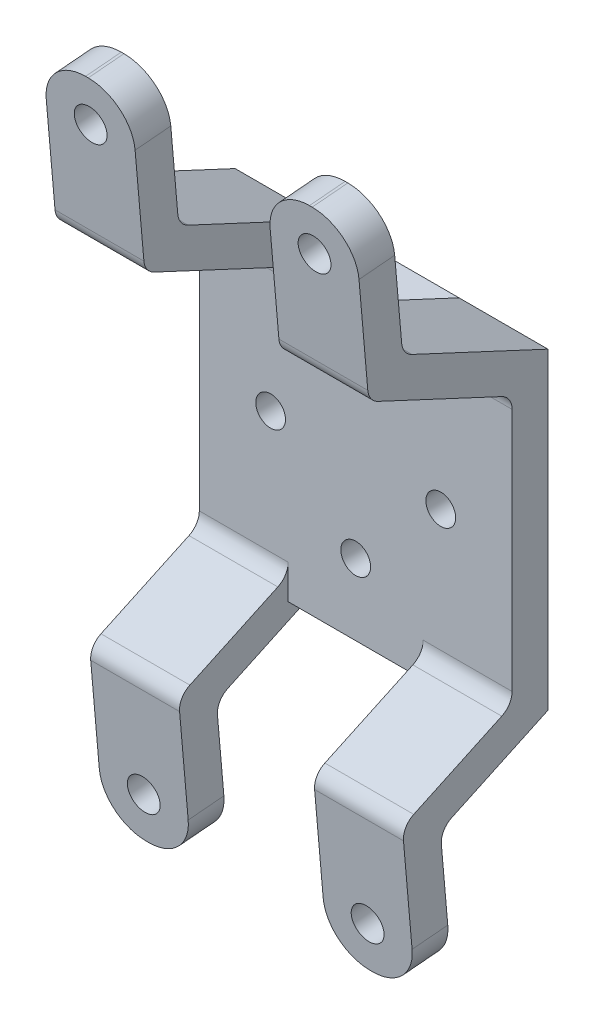
SolidWorks part; units mm, degrees
ref_plane "Front Plane" through (0, 0, 0) normal (0, 0, 1) x (1, 0, 0)
ref_plane "Top Plane" through (0, 0, 0) normal (0, 1, 0) x (1, 0, 0)
ref_plane "Right Plane" through (0, 0, 0) normal (1, 0, 0) x (0, 0, -1)
sketch "Sketch1" plane through (0, 0, 0) normal (0, 0, 1) x (1, 0, 0)
  line L0 (0, 9.5) -> (-9.5, 0) construction
  line L1 (-17.4625, -17.4625) -> (17.4625, -17.4625)
  line L2 (-17.4625, -17.4625) -> (-17.4625, 17.4625)
  line L3 (-17.4625, 17.4625) -> (17.4625, 17.4625)
  line L4 (17.4625, -17.4625) -> (17.4625, 17.4625)
  line L5 (-17.4625, -17.4625) -> (17.4625, 17.4625) construction
  line L6 (-17.4625, 17.4625) -> (17.4625, -17.4625) construction
  line L7 (-9.5, 0) -> (0, -9.5) construction
  line L8 (0, -9.5) -> (9.5, 0) construction
  line L9 (9.5, 0) -> (0, 9.5) construction
  line L10 (0, 9.5) -> (0, -9.5)
  circle A0 centre (0, 9.5) radius 1.6625
  circle A1 centre (9.5, 0) radius 1.6625
  circle A2 centre (-9.5, 0) radius 1.6625
  circle A3 centre (0, -9.5) radius 1.6625
  point P0 (0, 0)
  dimension "D3" = 3.325
  dimension "D1" = 34.925
  dimension "D2" = 19
sketch "Sketch4" plane through (0, 0, 0) normal (1, 0, 0) x (0, 0, -1)
  line L0 (0, 0) -> (-2.8754, 32.8656) construction
  line L1 (0, 19.2087) -> (0, -19.2087) construction
  dimension "D1" = 5
ref_plane "Plane1" through (0, 0, 0) normal (0, 0.0872, -0.9962) x (0, 0.9962, 0.0872)
ref_plane "Plane2" through (0, -0.8716, 9.9619) normal (0, 0.0872, -0.9962) x (0, 0.9962, 0.0872)
extrude "Boss-Extrude4" add sketch "Sketch1" against normal blind 4 separate body
sketch "Sketch7" plane through (-17.4625, 0, 0) normal (-1, 0, 0) x (0, 0, 1)
  line L0 (0, 14.9142) -> (11.8255, 20.4285)
  line L1 (8.0201, -23.0675) -> (6.7627, -37.4389)
  line L2 (-4, 17.4625) -> (12.228, 25.0297)
  line L3 (0, -14.9142) -> (8.391, -18.827)
  line L4 (-4, -17.4625) -> (8.0201, -23.0675)
  line L5 (0, -17.4625) -> (0, 17.4625) construction
  line L6 (11.8255, 20.4285) -> (12.228, 25.0297) construction
  line L9 (8.391, -18.827) -> (8.0201, -23.0675) construction
  line L10 (0, -14.9142) -> (-4, -17.4625)
  line L11 (-4, 17.4625) -> (0, 14.9142)
  line L12 (13.0378, 34.2851) -> (6.8861, -36.0283) construction
  line L13 (12.228, 25.0297) -> (13.5282, 39.8907)
  line L14 (13.5282, 39.8907) -> (17.513, 39.5421)
  line L15 (17.513, 39.5421) -> (16.0115, 22.3805)
  line L16 (16.0115, 22.3805) -> (11.8255, 20.4285)
  line L17 (6.7627, -37.4389) -> (10.7475, -37.7875)
  line L18 (10.7475, -37.7875) -> (12.2489, -20.626)
  line L19 (12.2489, -20.626) -> (8.391, -18.827)
  line M5 (0, -17.4625) -> (0, 17.4625)
  line M6 (0, 17.4625) -> (-4, 17.4625)
  line M8 (-4, -17.4625) -> (0, -17.4625)
  dimension "D1" = 115
  dimension "D2" = 115
  dimension "D3" = 4
  dimension "D4" = 4
  dimension "D5" = 4
  dimension "D6" = 77.625
extrude "Boss-Extrude7" add sketch "Sketch7" against normal blind 9.925 contours L18 L19 L4 L1 L17 M5 M8 | L16 L15 L14 L13 L2 L0 M6 M5
hole_wizard "#6 Clearance Hole1" positions "Sketch8" profile "Sketch9" hole size "#6" standard "ANSI Inch" end condition through all
sketch "Sketch8" plane through (0, -1.2202, 13.9467) normal (0, -0.0872, 0.9962) x (1, 0, 0)
  line L0 (-17.4625, 36.1055) -> (-7.5375, 36.1055) construction
  line L2 (-17.4625, -31.8945) -> (-7.5375, -31.8945) construction
  line L4 (-12.5, 36.1055) -> (-12.5, -31.8945) construction
  line L10 (-12.5, 36.1055) -> (-12.5, 40.918) construction
  line L11 (-7.5375, 40.918) -> (-17.4625, 40.918) construction
  line L13 (-12.5, -31.8945) -> (-12.5, -36.707) construction
  line L14 (-7.5375, -36.707) -> (-17.4625, -36.707) construction
  line L15 (-17.4625, -36.707) -> (-17.4625, -19.4799) construction
  line L16 (-7.5375, -36.707) -> (-7.5375, -19.4799) construction
  line L17 (-17.4625, 40.918) -> (-17.4625, 23.6908) construction
  line L18 (-7.5375, 40.918) -> (-7.5375, 23.6908) construction
  point P0 (-12.5, 36.1055)
  point P2 (-12.5, -31.8945)
  dimension "D1" = 68
sketch "Sketch9" plane through (-12.5, 34.7479, 17.0935) normal (1, 0, 0) x (0, -0.9962, -0.0872)
  line L0 (0, 0) -> (0, 21.4615)
  line L1 (0, 21.4615) -> (1.8288, 21.4615)
  line L2 (1.8288, 21.4615) -> (1.8288, 0)
  line L5 (1.8288, 0) -> (0, 0)
  line L11 (0, -6.35) -> (0, 107.95) construction
  dimension "Thru Hole Dia." = 3.6576
  dimension "Thru Hole Depth" = 21.4615
fillet "Fillet1" radius 4.8125 4 edges at (-7.5375, -37.6132, 8.7551) (-17.4625, -37.6132, 8.7551) (-7.5375, 39.7164, 15.5206) (-17.4625, 39.7164, 15.5206)
fillet "Fillet2" radius 2 6 edges at (-12.5, 25.0297, 12.228) (-12.5, -23.0675, 8.0201) (-12.5, -20.626, 12.2489) (-12.5, 22.3805, 16.0115) (-12.5, -14.9142, 0) (-12.5, 14.9142, 0)
mirror "Mirror1" about plane through (0, 0, 0) normal (1, 0, 0) of "Fillet2", "Boss-Extrude7", "#6 Clearance Hole1", "Fillet1"
equation "\"od square tube\"= 1.375in"
equation "\"camera mount hole diameter\"= 0.1440in"
equation "\"cam mount hole separation\"= 45mm"
equation "\"D1@Sketch1\"=\"od square tube\""
equation "\"frame mount hole diameter\"= 3.125mm"
equation "\"tolerance\"= .2mm"
equation "\"D3@Sketch1\"= \"frame mount hole diameter\" + \"tolerance\""
equation "\"horizontal angle\"= 40"
equation "\"vertical angle\"= 5"
equation "\"frame mount hole separation\"= 19mm"
equation "\"washer counterbore\"= 4.7625mm + 0.05mm"
equation "\"D1@Sketch4\"=\"vertical angle\""
equation "\"D6@Sketch7\"=68+2*\"washer counterbore\""
equation "\"D1@Boss-Extrude7\"=((\"od square tube\"/2) - 12.50mm)*2"
equation "\"D1@Fillet1\"=\"washer counterbore\""
